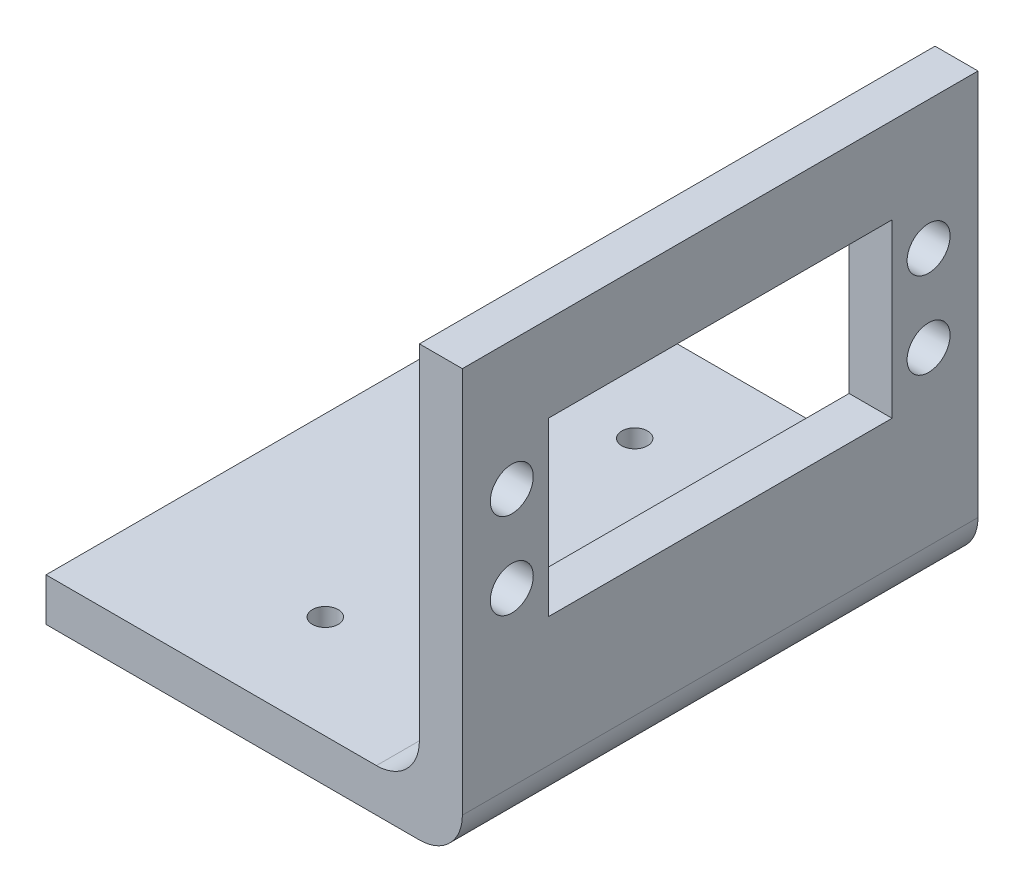
SolidWorks part; units mm, degrees
ref_plane "Front Plane" through (0, 0, 0) normal (0, 0, 1) x (1, 0, 0)
ref_plane "Top Plane" through (0, 0, 0) normal (0, 1, 0) x (1, 0, 0)
ref_plane "Right Plane" through (0, 0, 0) normal (1, 0, 0) x (0, 0, -1)
sketch "Sketch1" plane through (0, 0, 0) normal (0, 0, 1) x (1, 0, 0)
  line L0 (0, 0) -> (0, 50)
  line L1 (0, 50) -> (-5, 50)
  line L2 (-5, 50) -> (-5, 5)
  line L3 (-5, 5) -> (-48.45, 5)
  line L4 (-48.45, 5) -> (-48.45, 0)
  line L5 (-48.45, 0) -> (0, 0)
  dimension "D1" = 50
  dimension "D2" = 5
  dimension "D3" = 48.45
  dimension "D4" = 5
extrude "Boss-Extrude1" add sketch "Sketch1" against normal blind 60
sketch "Sketch2" plane through (0, 0, 0) normal (1, 0, 0) x (0, 0, -1)
  line L0 (0, 5) -> (60, 5) construction
  line L1 (0, 0) -> (0, 50) construction
  line L2 (60, 0) -> (60, 50) construction
  line L3 (60, 0) -> (0, 0) construction
  line L4 (0, 30) -> (60, 30) construction
  line L5 (30, 0) -> (30, 50) construction
  line L6 (50, 20) -> (10, 20)
  line L7 (50, 20) -> (50, 40)
  line L8 (50, 40) -> (10, 40)
  line L9 (10, 20) -> (10, 40)
  line L10 (50, 20) -> (10, 40) construction
  line L11 (50, 40) -> (10, 20) construction
  line L12 (60, 50) -> (0, 50) construction
  circle A1 centre (54.25, 35) radius 2.5
  circle A2 centre (54.25, 25) radius 2.5
  circle A3 centre (5.75, 25) radius 2.5
  circle A4 centre (5.75, 35) radius 2.5
  point P10 (30, 30)
  dimension "D4" = 5
  dimension "D1" = 5
  dimension "D2" = 20
  dimension "D3" = 40
  dimension "D5" = 5
  dimension "D6" = 48.5
  dimension "D7" = 20
extrude "Cut-Extrude1" cut sketch "Sketch2" against normal blind 10
sketch "Sketch3" plane through (0, 0, 0) normal (0, -1, 0) x (1, 0, 0)
  line L0 (-36.45, 0) -> (-36.45, -60) construction
  line L1 (-48.45, 0) -> (0, 0) construction
  line L2 (-48.45, -60) -> (0, -60) construction
  line L3 (-48.45, -60) -> (-48.45, 0) construction
  line L4 (-27.95, 0) -> (-27.95, -60) construction
  line L5 (-36.45, 0) -> (-19.45, 0) construction
  line L6 (-36.45, 0) -> (-36.45, -60) construction
  line L7 (-36.45, -60) -> (-19.45, -60) construction
  line L8 (-19.45, 0) -> (-19.45, -60) construction
  circle A0 centre (-27.95, -30) radius 1.5
  circle A1 centre (-27.95, -12) radius 1.5
  circle A2 centre (-27.95, -48) radius 1.5
  dimension "D3" = 3
  dimension "D4" = 18
  dimension "D1" = 12
  dimension "D2" = 17
  dimension "D5" = 18
extrude "Cut-Extrude2" cut sketch "Sketch3" against normal blind 10
ref_plane "Plane1" through (0, 0, -30) normal (0, 0, 1) x (1, 0, 0)
sketch "Sketch4" plane through (0, 0, -30) normal (0, 0, 1) x (1, 0, 0)
  line L0 (-5, 20) -> (-20, 5)
  line L1 (-5, 50) -> (-5, 5) construction
  line L2 (-5, 5) -> (-48.45, 5) construction
  line L3 (-5, 20) -> (0, 20) construction
  line L4 (0, 0) -> (0, 50) construction
  line L5 (-48.45, 0) -> (0, 0) construction
  dimension "D1" = 20
  dimension "D2" = 45
rib "Rib1" sketch "Sketch4" sketch "Sketch4" thickness 10 extrusion direction parallel to sketch draft on no parameters "D1"=10
fillet "Fillet1" radius 5 3 edges at (0, 0, -30) (-5, 5, -47.5) (-5, 5, -12.5)
